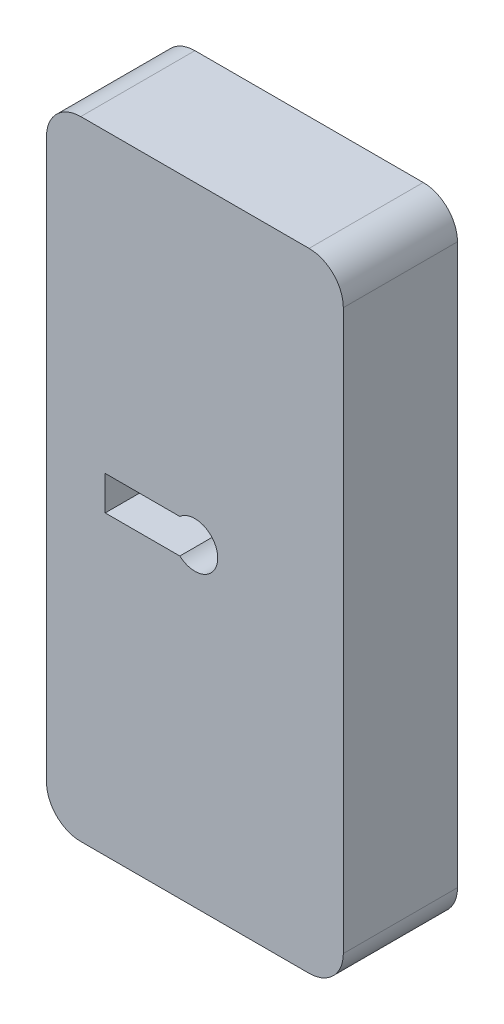
SolidWorks part; units mm, degrees
material "1.4006 (X10Cr13)"
ref_plane "Front Plane" through (0, 0, 0) normal (0, 0, 1) x (1, 0, 0)
ref_plane "Top Plane" through (0, 0, 0) normal (0, 1, 0) x (1, 0, 0)
ref_plane "Right Plane" through (0, 0, 0) normal (1, 0, 0) x (0, 0, -1)
sketch "Sketch1" plane through (0, 0, 0) normal (0, 0, 1) x (1, 0, 0)
  line L0 (0, -47.5) -> (0, 7.5) construction
  line L1 (-10, -47.5) -> (10, -47.5)
  line L2 (-13, -44.5) -> (-13, 4.5)
  line L3 (-10, 7.5) -> (10, 7.5)
  line L4 (13, -44.5) -> (13, 4.5)
  line L5 (-13, -20) -> (13, -20) construction
  line L6 (0, -5) -> (0, -35) construction
  line L7 (-13, -20) -> (13, -20) construction
  arc A2 (-12.1777, -15.45) -> (12.1777, -15.45) centre (0, -20) ccw construction
  arc A3 (-13, 4.5) -> (-10, 7.5) centre (-10, 4.5) cw
  arc A4 (10, 7.5) -> (13, 4.5) centre (10, 4.5) cw
  arc A5 (13, -44.5) -> (10, -47.5) centre (10, -44.5) cw
  arc A6 (-13, -44.5) -> (-10, -47.5) centre (-10, -44.5) ccw
  point P10 (0, -20)
  dimension "D1" = 3
  dimension "D2" = 55
extrude "Boss-Extrude1" add sketch "Sketch1" along normal blind 10
sketch "Sketch5" plane through (0, 0, 0) normal (0, 0, -1) x (-1, 0, 0)
  circle A0 centre (0, -20) radius 4
  arc A5 (3.7081, -18.5) -> (3.7081, -21.5) centre (0, -20) ccw construction
extrude "Cut-Extrude3" cut sketch "Sketch5" against normal blind 5
sketch "Sketch2" plane through (0, 0, 10) normal (0, 0, 1) x (1, 0, 0)
  line L0 (0, -5) -> (0, -35) construction
  line L1 (-1.3229, -18.5) -> (-7.8581, -18.5)
  line L2 (-7.8581, -18.5) -> (-7.8581, -21.5)
  line L3 (-7.8581, -21.5) -> (-1.3229, -21.5)
  line L4 (-1.3229, -18.5) -> (-3.7081, -18.5) construction
  line L5 (-3.7081, -21.5) -> (-1.3229, -21.5) construction
  arc A0 (-1.3229, -21.5) -> (-1.3229, -18.5) centre (0, -20) ccw
  arc A1 (-1.3229, -21.5) -> (-1.3229, -18.5) centre (0, -20) ccw construction
  circle A2 centre (0, -20) radius 8 construction
sketch "Sketch6" plane through (0, -20, 65) normal (1, 0, 0) x (0, -1, 0)
  line L0 (0, 65) -> (0, 55) construction
  line L1 (24.5, 55) -> (-24.5, 55) construction
extrude "Cut-Extrude1" cut sketch "Sketch2" against normal up to surface (10 mm away) up to face at (-4, -20, 0)
sketch "Sketch3" plane through (0, 0, 0) normal (0, 0, -1) x (-1, 0, 0)
  line L0 (0, 7.5) -> (0, -5.5) construction
  line L1 (10, 7.5) -> (-10, 7.5) construction
  line L4 (0, 35.2) -> (0, -35.2) construction
  line L5 (0, -5.5) -> (0, -9) construction
  line L6 (0, -9) -> (0, -12.5) construction
  circle A18 centre (0, -5.5) radius 1.65
  circle A19 centre (0, -9) radius 1.65
  circle A20 centre (0, -12.5) radius 1.65
  dimension "D2" = 3.5
  dimension "D1" = 3.3
  dimension "D3" = 13
extrude "Cut-Extrude2" cut sketch "Sketch3" against normal blind 3.3
fillet "Fillet1" radius 1.65 3 edges at (-1.65, -9, 3.3) (-1.65, -12.5, 3.3) (-1.65, -5.5, 3.3)
